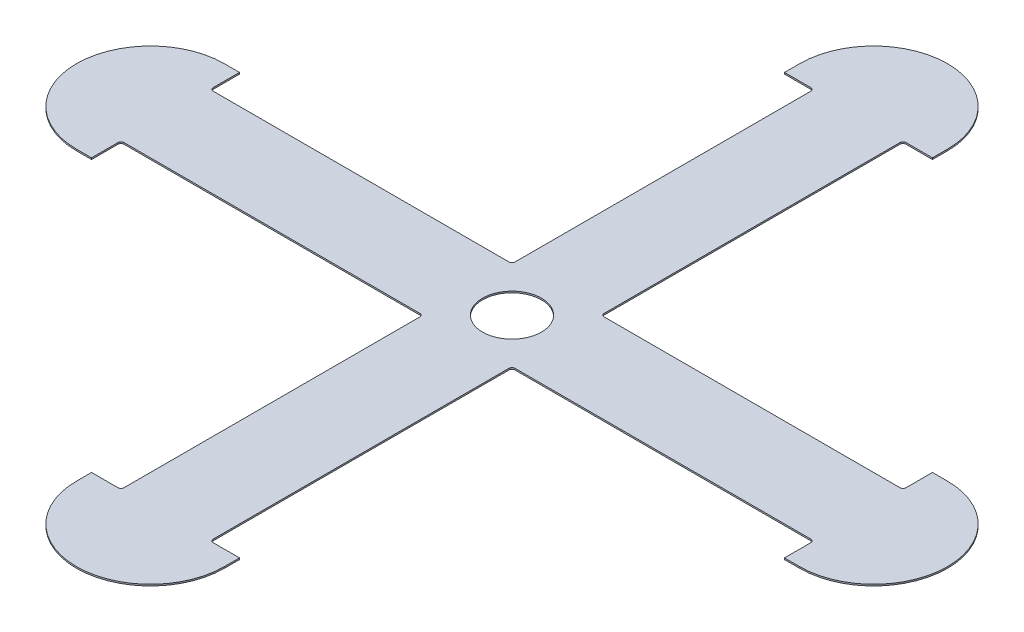
SolidWorks part; units mm, degrees
ref_plane "Front Plane" through (0, 0, 0) normal (0, 0, 1) x (1, 0, 0)
ref_plane "Top Plane" through (0, 0, 0) normal (0, 1, 0) x (1, 0, 0)
ref_plane "Right Plane" through (0, 0, 0) normal (1, 0, 0) x (0, 0, -1)
sketch "Sketch1" plane through (0, 0, 0) normal (0, 1, 0) x (1, 0, 0)
  line L0 (-55, 0) -> (55, 0) construction
  line L1 (-11.225, -11.225) -> (11.225, -11.225)
  line L2 (-11.225, -11.225) -> (-11.225, 11.225)
  line L3 (-11.225, 11.225) -> (11.225, 11.225)
  line L4 (11.225, -11.225) -> (11.225, 11.225)
  line L5 (-11.225, -11.225) -> (11.225, 11.225) construction
  line L6 (-11.225, 11.225) -> (11.225, -11.225) construction
  line L7 (-11.225, 11.225) -> (-1.725, 11.225)
  line L8 (-11.225, 11.225) -> (-11.225, 1.725)
  line L9 (-11.225, 1.725) -> (-1.725, 1.725)
  line L10 (-1.725, 11.225) -> (-1.725, 1.725)
  line L11 (-1.725, -11.225) -> (-1.725, -1.725)
  line L12 (-11.225, -1.725) -> (-1.725, -1.725)
  line L13 (0, -55) -> (0, 55) construction
  line L14 (1.725, -11.225) -> (1.725, -1.725)
  line L15 (11.225, -1.725) -> (1.725, -1.725)
  line L16 (1.725, 11.225) -> (1.725, 1.725)
  line L17 (11.225, 1.725) -> (1.725, 1.725)
  line L18 (-1.475, 1.475) -> (-11.225, 1.475)
  line L19 (11.475, -11.475) -> (-11.475, -11.475)
  line L20 (11.475, -11.475) -> (11.475, 11.475)
  line L21 (11.475, 11.475) -> (-11.475, 11.475)
  line L22 (-11.475, -11.475) -> (-11.475, 11.475)
  line L23 (11.475, -11.475) -> (-11.475, 11.475) construction
  line L24 (11.475, 11.475) -> (-11.475, -11.475) construction
  line L25 (11.225, -1.475) -> (1.475, -1.475)
  line L26 (11.225, -1.475) -> (11.225, 1.475)
  line L27 (11.225, 1.475) -> (1.475, 1.475)
  line L28 (-11.225, -1.475) -> (-11.225, 1.475)
  line L29 (11.225, -1.475) -> (-11.225, 1.475) construction
  line L30 (11.225, 1.475) -> (-11.225, -1.475) construction
  line L31 (-1.475, -11.225) -> (1.475, -11.225)
  line L32 (-1.475, -11.225) -> (-1.475, -1.475)
  line L33 (-1.475, 11.225) -> (1.475, 11.225)
  line L34 (1.475, -11.225) -> (1.475, -1.475)
  line L35 (-1.475, -11.225) -> (1.475, 11.225) construction
  line L36 (-1.475, 11.225) -> (1.475, -11.225) construction
  line L37 (-1.475, 1.475) -> (-1.475, 11.225)
  line L38 (-1.475, -1.475) -> (-11.225, -1.475)
  line L39 (1.475, 1.475) -> (1.475, 11.225)
  line L40 (-11.475, 0) -> (-15.585, 0) construction
  line L41 (1.725, 1.725) -> (-1.725, 1.725)
  line L42 (1.725, 1.725) -> (1.725, -1.725)
  line L43 (1.725, -1.725) -> (-1.725, -1.725)
  line L44 (-1.725, 1.725) -> (-1.725, -1.725)
  line L45 (1.725, 1.725) -> (-1.725, -1.725) construction
  line L46 (1.725, -1.725) -> (-1.725, 1.725) construction
  line L47 (-11.475, -2.45) -> (-11.725, -2.45)
  line L48 (-11.475, 1.45) -> (-11.725, 1.45)
  line L49 (-11.475, 1.45) -> (-11.475, 2.45)
  line L50 (-11.475, 2.45) -> (-11.725, 2.45)
  line L51 (-11.725, 1.45) -> (-11.725, 2.45)
  line L52 (-11.725, -1.45) -> (-11.725, -2.45)
  line L53 (-11.475, -1.45) -> (-11.725, -1.45)
  line L54 (-11.475, -1.45) -> (-11.475, -2.45)
  line L55 (1.45, 11.475) -> (2.45, 11.475)
  line L56 (1.45, 11.475) -> (1.45, 11.725)
  line L57 (1.45, 11.725) -> (2.45, 11.725)
  line L58 (2.45, 11.475) -> (2.45, 11.725)
  line L59 (-2.45, 11.475) -> (-2.45, 11.725)
  line L60 (-1.45, 11.725) -> (-2.45, 11.725)
  line L61 (-1.45, 11.475) -> (-1.45, 11.725)
  line L62 (-1.45, 11.475) -> (-2.45, 11.475)
  line L63 (11.475, -1.45) -> (11.475, -2.45)
  line L64 (11.475, -1.45) -> (11.725, -1.45)
  line L65 (11.725, -1.45) -> (11.725, -2.45)
  line L66 (11.475, -2.45) -> (11.725, -2.45)
  line L67 (11.475, 2.45) -> (11.725, 2.45)
  line L68 (11.725, 1.45) -> (11.725, 2.45)
  line L69 (11.475, 1.45) -> (11.725, 1.45)
  line L70 (11.475, 1.45) -> (11.475, 2.45)
  line L71 (-1.45, -11.475) -> (-2.45, -11.475)
  line L72 (-1.45, -11.475) -> (-1.45, -11.725)
  line L73 (-1.45, -11.725) -> (-2.45, -11.725)
  line L74 (-2.45, -11.475) -> (-2.45, -11.725)
  line L75 (2.45, -11.475) -> (2.45, -11.725)
  line L76 (1.45, -11.725) -> (2.45, -11.725)
  line L77 (1.45, -11.475) -> (1.45, -11.725)
  line L78 (1.45, -11.475) -> (2.45, -11.475)
  line L79 (2.45, 11.725) -> (-2.45, 11.725)
  line L80 (-11.725, 2.45) -> (-11.975, 2.45)
  line L81 (-11.725, 2.45) -> (-11.725, -2.45)
  line L82 (-11.725, -2.45) -> (-11.975, -2.45)
  line L83 (-11.975, 2.45) -> (-11.975, -2.45)
  line L84 (2.45, 11.725) -> (2.45, 11.975)
  line L85 (2.45, 11.975) -> (-2.45, 11.975)
  line L86 (-2.45, 11.725) -> (-2.45, 11.975)
  line L87 (11.725, -2.45) -> (11.725, 2.45)
  line L88 (11.725, -2.45) -> (11.975, -2.45)
  line L89 (11.975, -2.45) -> (11.975, 2.45)
  line L90 (11.725, 2.45) -> (11.975, 2.45)
  line L91 (-2.45, -11.725) -> (2.45, -11.725)
  line L92 (-2.45, -11.725) -> (-2.45, -11.975)
  line L93 (-2.45, -11.975) -> (2.45, -11.975)
  line L94 (2.45, -11.725) -> (2.45, -11.975)
  circle A0 centre (0, 0) radius 0.975
  point P0 (0, 0)
  point P77 (0, 0)
  point P92 (0, 0)
  dimension "D3" = 1.95
  dimension "D1" = 22.45
  dimension "D2" = 9.5
  dimension "D4" = 0.25
  dimension "D5" = 0.25
  dimension "D6" = 0.25
  dimension "D7" = 0.25
  dimension "D8" = 0.25
  dimension "D9" = 1.45
  dimension "D10" = 1
  dimension "D12" = 0.25
  dimension "D11" = 4
  dimension "D13" = 4
extrude "Boss-Extrude5" add sketch "Sketch1" along normal blind 0.05 contours L22 L19 L20 L21 L4 L1 L2 L3 | L32 L43 L11 L1 | L44 L38 L2 L12 | L18 L44 L38 L32 L43 L34 L25 L42 L27 L39 L41 L37 A0 | L38 L44 L43 L32 | L43 L42 L25 L34 | L25 L42 L15 L4 | L14 L43 L34 L1 | L42 L41 L39 L27 | L17 L42 L27 L4 | L41 L16 L3 L39 | L41 L44 L18 L37 | L44 L9 L2 L18 | L41 L37 L3 L10 | L22 L53 L52 L47 | L51 L48 L22 L50 | L20 L66 L65 L64 | L20 L69 L68 L67 | L19 L77 L76 L75 | L19 L74 L73 L72 | L21 L58 L57 L56 | L21 L61 L60 L59 | L80 L83 L82 L52 L81 L51 | L94 L76 L91 L73 L92 L93 | L90 L68 L87 L65 L88 L89 | L86 L60 L79 L57 L84 L85
sketch "Sketch2" plane through (0, 0.05, 0) normal (0, 1, 0) x (1, 0, 0)
  line L18 (-1.725, 1.475) -> (-11.225, 1.475) construction
  line L19 (-11.475, 11.475) -> (-1.575, 11.475)
  line L20 (-11.475, 11.475) -> (-11.475, 1.575)
  line L21 (-11.375, 1.475) -> (-1.575, 1.475)
  line L22 (-1.475, 11.375) -> (-1.475, 1.575)
  line L23 (-1.475, 1.725) -> (-1.475, 11.225) construction
  line L24 (11.475, 11.475) -> (1.575, 11.475)
  line L25 (11.475, 11.475) -> (11.475, 1.575)
  line L26 (11.375, 1.475) -> (1.575, 1.475)
  line L27 (1.475, 11.375) -> (1.475, 1.575)
  line L28 (11.475, -11.475) -> (11.475, -1.575)
  line L29 (11.475, -11.475) -> (1.575, -11.475)
  line L30 (1.475, -11.375) -> (1.475, -1.575)
  line L31 (11.375, -1.475) -> (1.575, -1.475)
  line L32 (-11.475, -11.475) -> (-1.575, -11.475)
  line L33 (-11.475, -11.475) -> (-11.475, -1.575)
  line L34 (-11.375, -1.475) -> (-1.575, -1.475)
  line L35 (-1.475, -11.375) -> (-1.475, -1.575)
  arc A12 (-11.475, 1.575) -> (-11.375, 1.475) centre (-11.375, 1.575) ccw
  arc A13 (-1.575, 1.475) -> (-1.475, 1.575) centre (-1.575, 1.575) ccw
  arc A14 (-1.475, 11.375) -> (-1.575, 11.475) centre (-1.575, 11.375) ccw
  arc A15 (1.575, 11.475) -> (1.475, 11.375) centre (1.575, 11.375) ccw
  arc A16 (11.375, 1.475) -> (11.475, 1.575) centre (11.375, 1.575) ccw
  arc A17 (1.475, 1.575) -> (1.575, 1.475) centre (1.575, 1.575) ccw
  arc A18 (11.475, -1.575) -> (11.375, -1.475) centre (11.375, -1.575) ccw
  arc A19 (1.475, -11.375) -> (1.575, -11.475) centre (1.575, -11.375) ccw
  arc A20 (1.575, -1.475) -> (1.475, -1.575) centre (1.575, -1.575) ccw
  arc A21 (-1.575, -11.475) -> (-1.475, -11.375) centre (-1.575, -11.375) ccw
  arc A22 (-11.375, -1.475) -> (-11.475, -1.575) centre (-11.375, -1.575) ccw
  arc A23 (-1.475, -1.575) -> (-1.575, -1.475) centre (-1.575, -1.575) ccw
  point P48 (0, 0)
  dimension "D1" = 0.1
extrude "Cut-Extrude1" cut sketch "Sketch2" against normal through all contours A12 L21 A13 L22 A14 L19 L20 | L24 A15 L27 A17 L26 A16 L25 | L28 A18 L31 A20 L30 A19 L29 | L32 A21 L35 A23 L34 A22 L33
sketch "Sketch4" plane through (0, 0.05, 0) normal (0, 1, 0) x (1, 0, 0)
  line L0 (-11.975, 2.45) -> (-11.975, -2.45) construction
  line L1 (-11.225, -1.475) -> (-1.725, -1.475)
  line L2 (-11.225, -1.475) -> (-11.225, 1.475)
  line L3 (-11.225, 1.475) -> (-1.725, 1.475)
  line L4 (-1.725, -1.475) -> (-1.725, 1.475)
  line L5 (-11.975, 2.45) -> (-11.975, -2.45)
  line L6 (2.45, 11.975) -> (-2.45, 11.975)
  line L7 (-1.475, 11.225) -> (1.475, 11.225)
  line L8 (-1.475, 11.225) -> (-1.475, 1.725)
  line L9 (-1.475, 1.725) -> (1.475, 1.725)
  line L10 (1.475, 11.225) -> (1.475, 1.725)
  line L11 (11.975, -2.45) -> (11.975, 2.45)
  line L12 (11.225, 1.475) -> (11.225, -1.475)
  line L13 (11.225, 1.475) -> (1.725, 1.475)
  line L14 (1.725, 1.475) -> (1.725, -1.475)
  line L15 (11.225, -1.475) -> (1.725, -1.475)
  line L16 (-2.45, -11.975) -> (2.45, -11.975)
  line L17 (1.475, -11.225) -> (-1.475, -11.225)
  line L18 (1.475, -11.225) -> (1.475, -1.725)
  line L19 (1.475, -1.725) -> (-1.475, -1.725)
  line L20 (-1.475, -11.225) -> (-1.475, -1.725)
  line L21 (1.475, 11.225) -> (-1.475, 11.225)
  line L22 (-11.225, 1.475) -> (-11.975, 1.475)
  line L23 (-11.225, 1.475) -> (-11.225, -1.475)
  line L24 (-11.225, -1.475) -> (-11.975, -1.475)
  line L25 (-11.975, 1.475) -> (-11.975, -1.475)
  line L26 (1.475, 11.225) -> (1.475, 11.975)
  line L27 (1.475, 11.975) -> (-1.475, 11.975)
  line L28 (-1.475, 11.225) -> (-1.475, 11.975)
  line L29 (11.225, -1.475) -> (11.225, 1.475)
  line L30 (11.225, -1.475) -> (11.975, -1.475)
  line L31 (11.975, -1.475) -> (11.975, 1.475)
  line L32 (11.225, 1.475) -> (11.975, 1.475)
  line L33 (-1.475, -11.225) -> (1.475, -11.225)
  line L34 (-1.475, -11.225) -> (-1.475, -11.975)
  line L35 (-1.475, -11.975) -> (1.475, -11.975)
  line L36 (1.475, -11.225) -> (1.475, -11.975)
  arc A0 (-11.975, 2.45) -> (-11.975, -2.45) centre (-11.975, 0) ccw
  arc A1 (2.45, 11.975) -> (-2.45, 11.975) centre (0, 11.975) ccw
  arc A2 (11.975, -2.45) -> (11.975, 2.45) centre (11.975, 0) ccw
  arc A3 (-2.45, -11.975) -> (2.45, -11.975) centre (0, -11.975) ccw
  point P37 (0, 0)
  point P52 (0, 0)
  line M8 (-1.725, 1.475) -> (-1.725, -1.475)
  line M12 (-1.475, -1.725) -> (1.475, -1.725)
  line M16 (1.725, -1.475) -> (1.725, 1.475)
  line M20 (1.475, 1.725) -> (-1.475, 1.725)
extrude "Boss-Extrude9" add sketch "Sketch4" against normal up to surface (0.05 mm away) contours L5 A0 | L24 L2 L22 L5 | L3 L2 L1 M8 | L15 L12 L13 M16 | L10 L7 L8 M20 | L11 A2 | L16 A3 | L6 A1 | L28 L7 L26 L6 | L32 L12 L30 L11 | L20 L17 L18 M12 | L36 L17 L34 L16 up to face at (0, 0, 0.975)
